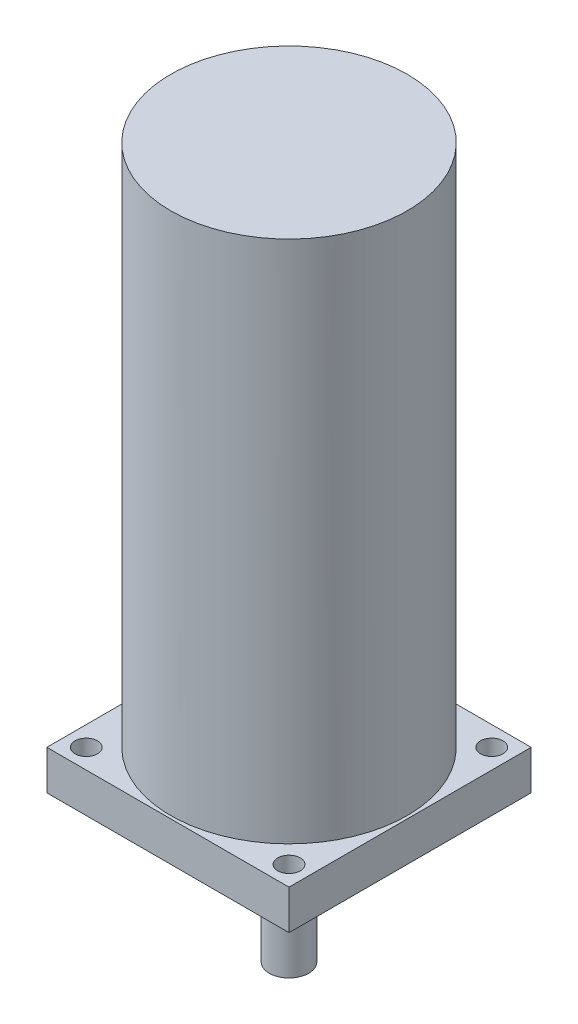
SolidWorks part; units mm, degrees
ref_plane "Front Plane" through (0, 0, 0) normal (0, 0, 1) x (1, 0, 0)
ref_plane "Top Plane" through (0, 0, 0) normal (0, 1, 0) x (1, 0, 0)
ref_plane "Right Plane" through (0, 0, 0) normal (1, 0, 0) x (0, 0, -1)
sketch "Sketch1" plane through (0, 0, 0) normal (0, 1, 0) x (1, 0, 0)
  circle A0 centre (0, 0) radius 21
  dimension "D1" = 42
extrude "Boss-Extrude1" add sketch "Sketch1" along normal blind 100 contours A0
sketch "Sketch2" plane through (0, 100, 0) normal (0, 1, 0) x (1, 0, 0)
  circle A0 centre (0, 0) radius 10
  dimension "D1" = 20
sketch "Sketch3" plane through (0, 0, 0) normal (0, -1, 0) x (1, 0, 0)
  circle A0 centre (0, 0) radius 3.5
  dimension "D1" = 7
extrude "Boss-Extrude3" add sketch "Sketch3" along normal blind 26
sketch "Sketch4" plane through (0, 0, 0) normal (0, -1, 0) x (1, 0, 0)
  circle A0 centre (0, 0) radius 7
  dimension "D1" = 14
extrude "Boss-Extrude4" add sketch "Sketch4" along normal blind 7
sketch "Sketch5" plane through (0, 0, 0) normal (0, -1, 0) x (1, 0, 0)
  line L1 (-21.5, 21.5) -> (21.5, 21.5)
  line L2 (-21.5, 21.5) -> (-21.5, -21.5)
  line L3 (-21.5, -21.5) -> (21.5, -21.5)
  line L4 (21.5, 21.5) -> (21.5, -21.5)
  line L5 (-21.5, 21.5) -> (21.5, -21.5) construction
  line L6 (-21.5, -21.5) -> (21.5, 21.5) construction
  point P0 (0, 0)
  dimension "D1" = 43
extrude "Boss-Extrude5" add sketch "Sketch5" against normal blind 7
sketch "Sketch6" plane through (0, 0, 0) normal (0, -1, 0) x (1, 0, 0)
  line L1 (-18, -18) -> (18, -18)
  line L2 (-18, -18) -> (-18, 18)
  line L3 (-18, 18) -> (18, 18)
  line L4 (18, -18) -> (18, 18)
  line L5 (-18, -18) -> (18, 18) construction
  line L6 (-18, 18) -> (18, -18) construction
  circle A0 centre (18, 18) radius 2
  circle A1 centre (-18, 18) radius 2
  circle A2 centre (-18, -18) radius 2
  circle A3 centre (18, -18) radius 2
  point P0 (0, 0)
  dimension "D2" = 4
  dimension "D1" = 36
extrude "Cut-Extrude1" cut sketch "Sketch6" against normal through all both and the other way through all contours L2 A1 L3 | L3 A1 L2 | L2 A2 L1 | L1 A2 L2 | L4 A3 L1 | L1 A3 L4 | L3 A0 L4 | L4 A0 L3
